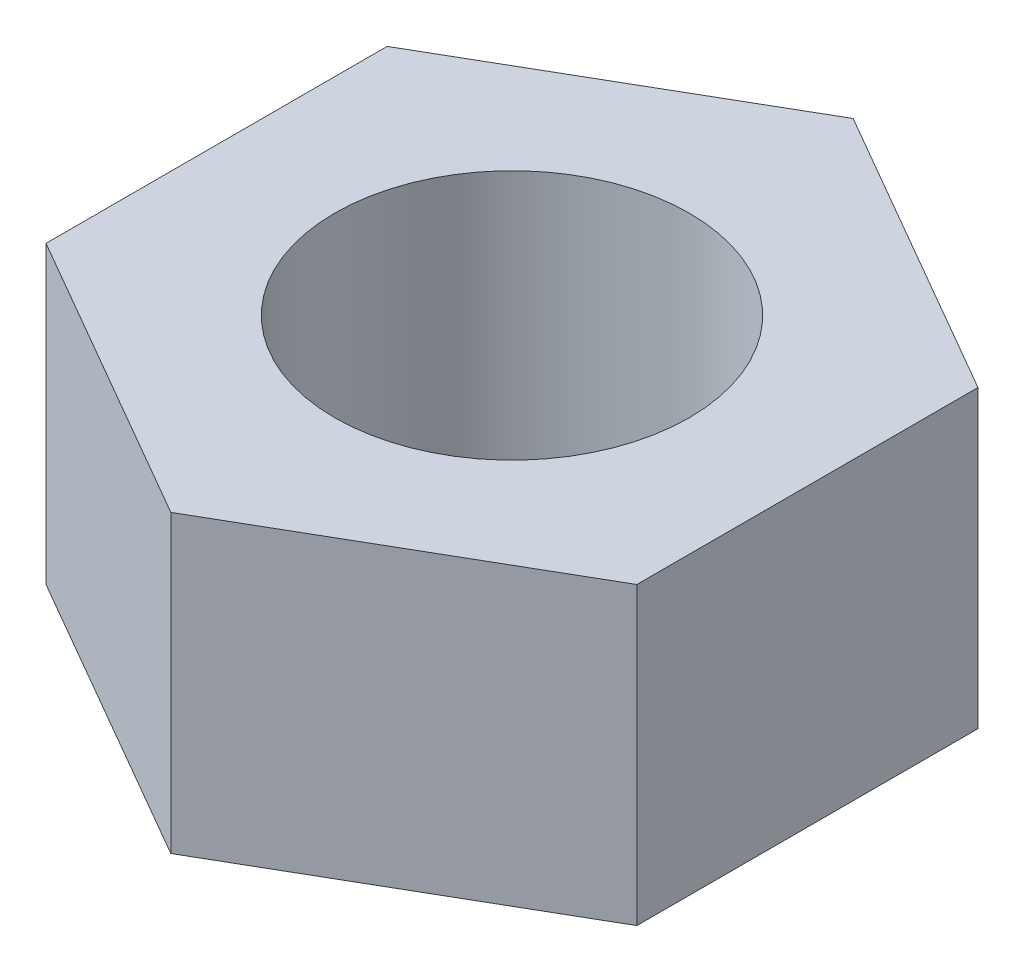
SolidWorks part; units mm, degrees
ref_plane "Front Plane" through (0, 0, 0) normal (0, 0, 1) x (1, 0, 0)
ref_plane "Top Plane" through (0, 0, 0) normal (0, 1, 0) x (1, 0, 0)
ref_plane "Right Plane" through (0, 0, 0) normal (1, 0, 0) x (0, 0, -1)
sketch "Sketch1" plane through (0, 0, 0) normal (0, 1, 0) x (1, 0, 0)
  line L1 (0, 2.8868) -> (-2.5, 1.4434)
  line L2 (-2.5, 1.4434) -> (-2.5, -1.4434)
  line L3 (-2.5, -1.4434) -> (0, -2.8868)
  line L4 (0, -2.8868) -> (2.5, -1.4434)
  line L5 (2.5, -1.4434) -> (2.5, 1.4434)
  line L6 (2.5, 1.4434) -> (0, 2.8868)
  circle A0 centre (0, 0) radius 2.5 construction
  dimension "D1" = 5
extrude "Boss-Extrude1" add sketch "Sketch1" along normal blind 2.5
sketch "Sketch2" plane through (0, 2.5, 0) normal (0, 1, 0) x (1, 0, 0)
  circle A0 centre (0, 0) radius 1.5
  dimension "D1" = 3
extrude "Cut-Extrude1" cut sketch "Sketch2" against normal blind 2.5
